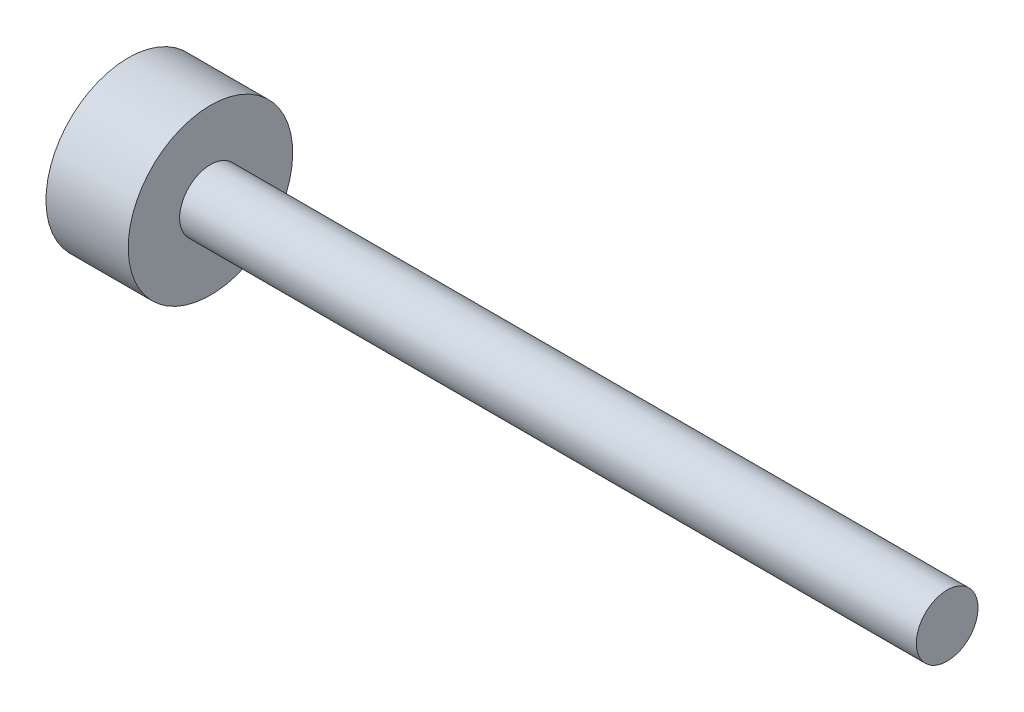
SolidWorks part; units mm, degrees
material "Delrin 2700 NC010, Low Viscosity Acetal Copolymer (SS)"
ref_plane "Front Plane" through (0, 0, 0) normal (0, 0, 1) x (1, 0, 0)
ref_plane "Top Plane" through (0, 0, 0) normal (0, 1, 0) x (1, 0, 0)
ref_plane "Right Plane" through (0, 0, 0) normal (1, 0, 0) x (0, 0, -1)
sketch "Sketch1" plane through (0, 0, 0) normal (0, 0, 1) x (1, 0, 0)
  line L0 (0, 0) -> (-19.914, 0) construction
  line L2 (0, 0) -> (-17.914, 0)
  line L3 (0, 0) -> (0, 0.75)
  line L4 (0, 0.75) -> (-17.914, 0.75)
  line L5 (-17.914, 0) -> (-17.914, 0.75)
  line L6 (-17.914, 0) -> (-19.914, 0)
  line L7 (-17.914, 0) -> (-17.914, 2)
  line L8 (-17.914, 2) -> (-19.914, 2)
  line L9 (-19.914, 0) -> (-19.914, 2)
  dimension "D1" = 2
  dimension "D2" = 17.914
  dimension "D3" = 2
  dimension "D4" = 0.75
revolve "Revolve1" add sketch "Sketch1" angle 360 about L0
